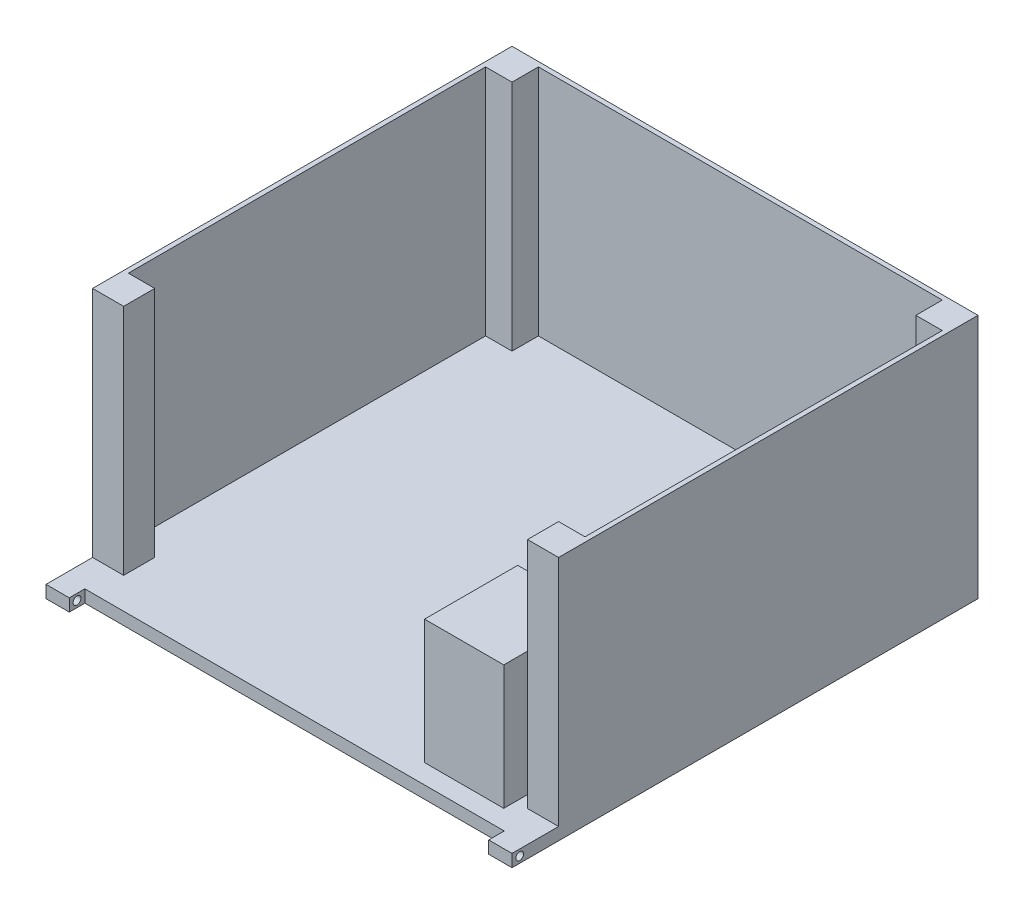
SolidWorks part; units mm, degrees
ref_plane "Front Plane" through (0, 0, 0) normal (0, 0, 1) x (1, 0, 0)
ref_plane "Top Plane" through (0, 0, 0) normal (0, 1, 0) x (1, 0, 0)
ref_plane "Right Plane" through (0, 0, 0) normal (1, 0, 0) x (0, 0, -1)
sketch "Sketch1" plane through (0, 0, 0) normal (0, 1, 0) x (1, 0, 0)
  line L0 (135, -150) -> (150, -150)
  line L1 (-150, 150) -> (150, 150)
  line L2 (-150, 150) -> (-150, -150)
  line L3 (-150, -150) -> (-135, -150)
  line L4 (150, 150) -> (150, -150)
  line L5 (-150, 150) -> (150, -150) construction
  line L6 (-150, -150) -> (150, 150) construction
  line L8 (-135, -140) -> (-135, -150)
  line L10 (135, -140) -> (135, -150)
  line L11 (-135, -140) -> (135, -140)
  point P0 (0, 0)
  dimension "D1" = 300
  dimension "D2" = 300
  dimension "D3" = 15
  dimension "D4" = 15
  dimension "D5" = 10
extrude "Boss-Extrude1" add sketch "Sketch1" along normal blind 8
sketch "Sketch2" plane through (0, 0, 0) normal (1, 0, 0) x (0, 0, -1)
  line L0 (-150, 0) -> (150, 0) construction
  line L1 (-150, 8) -> (-140.0671, 8) construction
  line L2 (-150, 8) -> (-150, 0) construction
  line L3 (-150, 0) -> (-140.0671, 0) construction
  line L4 (-140.0671, 8) -> (-140.0671, 0) construction
  line L5 (-150, 8) -> (-140.0671, 0) construction
  line L6 (-140.0671, 8) -> (-150, 0) construction
  circle A0 centre (-145.0335, 4) radius 2.5
  dimension "D1" = 5
extrude "Cut-Extrude1" cut sketch "Sketch2" against normal through all both and the other way through all
sketch "Sketch3" plane through (0, 8, 0) normal (0, 1, 0) x (1, 0, 0)
  line L0 (0, 78.3034) -> (0, -91.4601) construction
  line L1 (-150, 150) -> (-130, 150)
  line L2 (-150, 150) -> (-150, 130)
  line L3 (-150, 130) -> (-130, 130)
  line L4 (-130, 150) -> (-130, 130)
  line L5 (-81.4865, 0) -> (85.7305, 0) construction
  line L6 (130, 150) -> (130, 130)
  line L7 (150, 130) -> (130, 130)
  line L8 (150, 150) -> (150, 130)
  line L9 (150, 150) -> (130, 150)
  line L10 (-81.4865, 15) -> (85.7305, 15) construction
  line L11 (150, -120) -> (130, -120)
  line L12 (150, -120) -> (150, -100)
  line L13 (150, -100) -> (130, -100)
  line L14 (130, -120) -> (130, -100)
  line L15 (-130, -120) -> (-130, -100)
  line L16 (-150, -100) -> (-130, -100)
  line L17 (-150, -120) -> (-150, -100)
  line L18 (-150, -120) -> (-130, -120)
  dimension "D1" = 20
  dimension "D2" = 20
  dimension "D3" = 15
extrude "Boss-Extrude2" add sketch "Sketch3" along normal blind 150
sketch "Sketch4" plane through (0, 8, 0) normal (0, 1, 0) x (1, 0, 0)
  line L0 (-147, 147) -> (-147, -117)
  line L1 (-150, 150) -> (150, 150)
  line L2 (-150, 150) -> (-150, -120)
  line L4 (150, 150) -> (150, -120)
  line L6 (147, 147) -> (147, -117)
  line L7 (-147, 147) -> (147, 147)
  line L8 (-147, -117) -> (-150, -120)
  line L9 (147, -117) -> (150, -120)
  line L11 (-147, -117) -> (147, -117) construction
  line L12 (-150, -120) -> (150, -120) construction
  dimension "D1" = 3
extrude "Boss-Extrude3" add sketch "Sketch4" along normal blind 150
sketch "Sketch5" plane through (0, 8, 0) normal (0, 1, 0) x (1, 0, 0)
  line L1 (71.2297, -67.5348) -> (122.2297, -67.5348)
  line L2 (71.2297, -67.5348) -> (71.2297, -127.5348)
  line L3 (71.2297, -127.5348) -> (122.2297, -127.5348)
  line L4 (122.2297, -67.5348) -> (122.2297, -127.5348)
  dimension "D1" = 51
  dimension "D2" = 60
extrude "Boss-Extrude4" add sketch "Sketch5" along normal blind 80
sketch "Sketch7" plane through (71.2297, 0, 0) normal (-1, 0, 0) x (0, 0, 1)
  line L0 (127.5348, 48) -> (67.7501, 48) construction
  line L1 (127.5348, 88) -> (127.5348, 8) construction
  circle A0 centre (97.6425, 48) radius 4
  dimension "D1" = 8
extrude "Boss-Extrude5" add sketch "Sketch7" along normal blind 20
